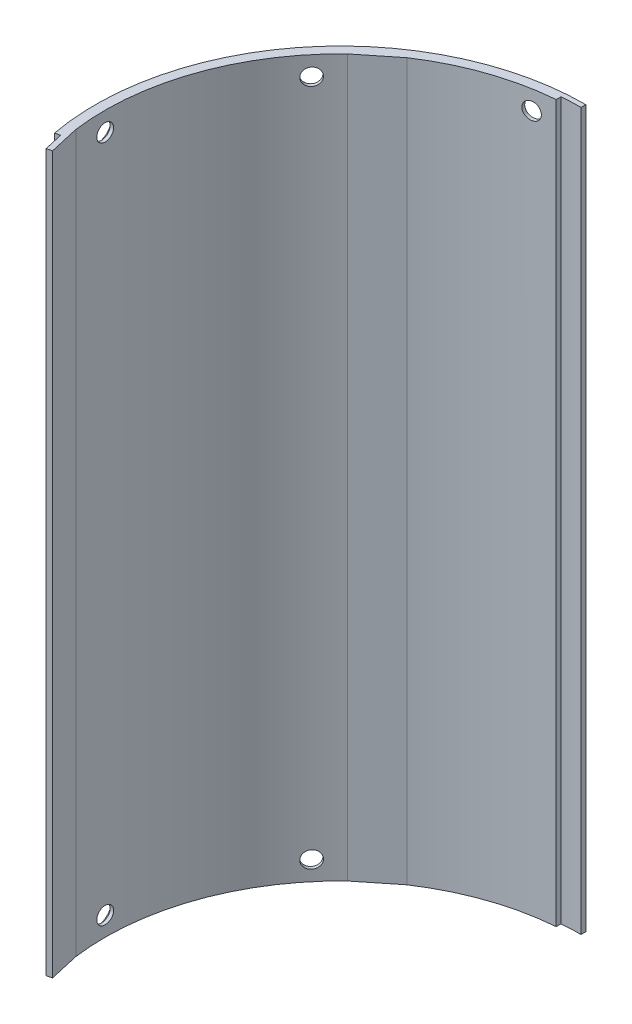
SolidWorks part; units mm, degrees
ref_plane "Спереди" through (0, 0, 0) normal (0, 0, 1) x (1, 0, 0)
ref_plane "Сверху" through (0, 0, 0) normal (0, 1, 0) x (1, 0, 0)
ref_plane "Справа" through (0, 0, 0) normal (1, 0, 0) x (0, 0, -1)
sketch "Эскиз1" plane through (0, 0, 0) normal (0, 1, 0) x (1, 0, 0)
  line L0 (0, -1000) -> (0, 49000) construction
  line L1 (48.5627, -6.5315) -> (47.1356, -12.7936) construction
  line L2 (48.2081, -13.038) -> (49.0969, -9.138) construction
  line L3 (47.1356, -12.7936) -> (48.2081, -13.038) construction
  line L4 (49.0969, -9.138) -> (50.1312, -9.3737) construction
  line L5 (48.5627, -6.5315) -> (47.1356, -12.7936) construction
  line L6 (48.2081, -13.038) -> (49.0969, -9.138) construction
  line L7 (47.1356, -12.7936) -> (48.2081, -13.038) construction
  line L8 (49.0969, -9.138) -> (50.1312, -9.3737) construction
  line L9 (-48.5627, -6.5315) -> (-47.1356, -12.7936)
  line L10 (-47.1356, -12.7936) -> (-48.2081, -13.038)
  line L11 (-48.2081, -13.038) -> (-49.0969, -9.138)
  line L12 (-49.0969, -9.138) -> (-50.1312, -9.3737)
  line L19 (-33.9524, 35.3303) -> (-27.0476, 40.8587) construction
  line L20 (-33.9524, 35.3303) -> (-27.0476, 40.8587)
  line L26 (0, 51) -> (0, 50) construction
  line L31 (0, 51) -> (0, 50)
  line L32 (-3.9968, 49.84) -> (-3.9968, 48.8367) construction
  line L33 (-3.9968, 49.84) -> (-3.9968, 48.8367)
  circle A0 centre (0, 0) radius 51 construction
  arc A1 (0, 51) -> (-50.1312, -9.3737) centre (0, 0) ccw
  arc A2 (48.5627, -6.5315) -> (33.9524, 35.3303) centre (0, 0) ccw construction
  arc A3 (48.5627, -6.5315) -> (33.9524, 35.3303) centre (0, 0) ccw construction
  arc A4 (-48.5627, -6.5315) -> (-33.9524, 35.3303) centre (0, 0) cw
  arc A5 (0, -51) -> (50.1312, -9.3737) centre (0, 0) ccw construction
  arc A6 (50.1312, -9.3737) -> (0, 51) centre (0, 0) ccw construction
  arc A7 (-23.8222, 42.8194) -> (-27.0476, 40.8587) centre (0, 0) ccw construction
  arc A8 (-23.8222, 42.8194) -> (-27.0476, 40.8587) centre (0, 0) ccw
  arc A9 (-50.1312, -9.3737) -> (0, -51) centre (0, 0) ccw construction
  arc A10 (-23.8222, 42.8194) -> (-3.9968, 48.8367) centre (0, 0) cw
  arc A11 (0, 50) -> (-3.9968, 49.84) centre (0, 0) ccw construction
  arc A12 (0, 50) -> (-3.9968, 49.84) centre (0, 0) ccw
extrude "Бобышка-Вытянуть1" add sketch "Эскиз1" along normal up to surface (149 mm away)
ref_plane "Плоскость5" through (-51, 0, 0) normal (-1, 0, 0) x (0, 0, 1)
sketch "Эскиз7" plane through (-51, 0, 0) normal (-1, 0, 0) x (0, 0, 1)
  circle A0 centre (0, 4) radius 3.25 construction
  circle A1 centre (0, 4) radius 3.25
extrude "Вырез-Вытянуть3" cut sketch "Эскиз7" against normal blind 1.3
sketch "Эскиз8" plane through (-49.7, 0, 0) normal (-1, 0, 0) x (0, 0, 1)
  circle A0 centre (0, 4) radius 1.75 construction
  circle A1 centre (0, 4) radius 1.75
extrude "Вырез-Вытянуть4" cut sketch "Эскиз8" against normal through all
pattern_circular "Круговой массив1" count 3 every 20 about axis through (0, 0, 0) along (0, 1, 0) skipping 1 of "Вырез-Вытянуть4", "Вырез-Вытянуть3"
sketch "Эскиз9" plane through (-51, 0, 0) normal (-1, 0, 0) x (0, 0, 1)
  circle A3 centre (0, 145) radius 3.25 construction
  circle A4 centre (0, 145) radius 3.25
extrude "Вырез-Вытянуть5" cut sketch "Эскиз9" against normal blind 1.3
sketch "Эскиз10" plane through (-49.7, 0, 0) normal (-1, 0, 0) x (0, 0, 1)
  circle A2 centre (0, 145) radius 1.75 construction
  circle A3 centre (0, 145) radius 1.75
extrude "Вырез-Вытянуть6" cut sketch "Эскиз10" against normal through all
pattern_circular "Круговой массив2" count 5 every 20 about axis through (0, 149, 0) along (0, 1, 0) skipping 1, 3 of "Вырез-Вытянуть6", "Вырез-Вытянуть5"
